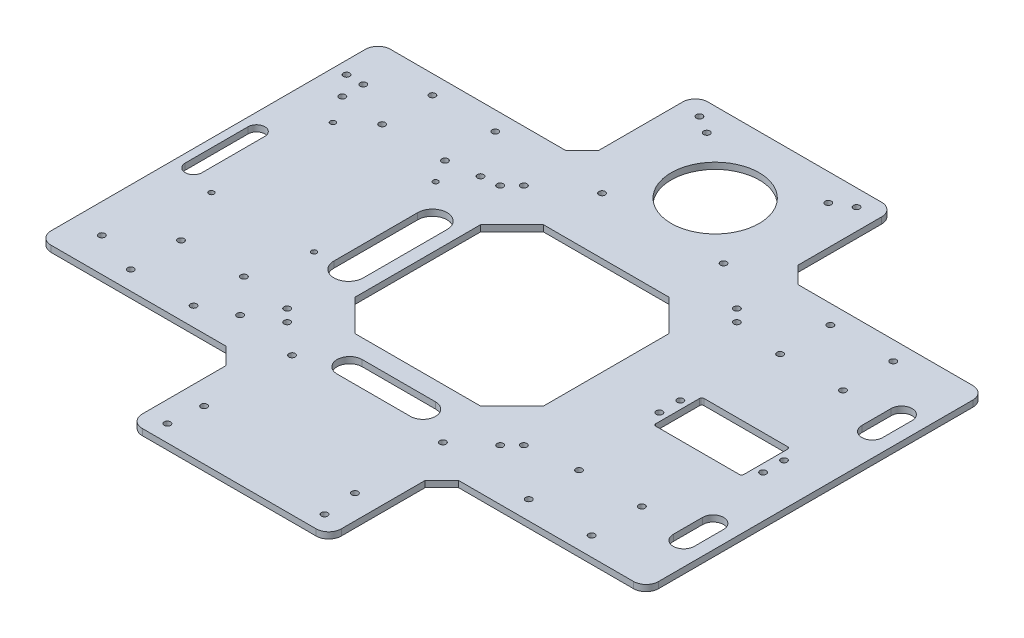
SolidWorks part; units mm, degrees
material "Thornel Mat VMA"
ref_plane "前视基准面" through (0, 0, 0) normal (0, 0, 1) x (1, 0, 0)
ref_plane "上视基准面" through (0, 0, 0) normal (0, 1, 0) x (1, 0, 0)
ref_plane "右视基准面" through (0, 0, 0) normal (1, 0, 0) x (0, 0, -1)
other "Configuration Table"
sketch "草图1" plane through (0, 0, 0) normal (0, 1, 0) x (1, 0, 0)
  line L0 (0, 0) -> (0, 135) construction
  line L1 (-145, -135) -> (145, -135)
  line L2 (-145, -135) -> (-145, 135)
  line L3 (-145, 135) -> (145, 135)
  line L4 (145, -135) -> (145, 135)
  line L5 (-145, -135) -> (145, 135) construction
  line L6 (-145, 135) -> (145, -135) construction
  line L7 (0, 0) -> (145, 0) construction
  line L8 (-47.5, 135) -> (-47.5, 81)
  line L9 (-47.5, 81) -> (-145, 81)
  line L10 (47.5, 81) -> (145, 81)
  line L11 (47.5, 135) -> (47.5, 81)
  line L12 (47.5, -81) -> (145, -81)
  line L13 (47.5, -135) -> (47.5, -81)
  line L14 (-47.5, -81) -> (-145, -81)
  line L15 (-47.5, -135) -> (-47.5, -81)
  point P0 (0, 0)
  dimension "D1" = 290
  dimension "D2" = 270
  dimension "D3" = 162
  dimension "D4" = 95
extrude "凸台-拉伸1" add sketch "草图1" along normal blind 3 contours L15 L1 L13 L12 L4 L10 L11 L3 L8 L9 L2 L14
sketch "草图2" plane through (0, 3, 0) normal (0, 1, 0) x (1, 0, 0)
  line L0 (0, 0) -> (145, 0) construction
  line L1 (145, -81) -> (145, 81) construction
  line L2 (0, 0) -> (0, 135) construction
  line L3 (-47.5, 135) -> (47.5, 135) construction
  line L4 (47.5, 81) -> (145, 81) construction
  circle A0 centre (110, 72) radius 1.5
  circle A1 centre (80, 72) radius 1.5
  circle A2 centre (80, 48) radius 1.5
  circle A3 centre (110, 48) radius 1.5
  circle A4 centre (110, -48) radius 1.5
  circle A5 centre (110, -72) radius 1.5
  circle A6 centre (80, -48) radius 1.5
  circle A7 centre (80, -72) radius 1.5
  circle A8 centre (-80, -72) radius 1.5
  circle A9 centre (-80, -48) radius 1.5
  circle A10 centre (-110, -72) radius 1.5
  circle A11 centre (-110, -48) radius 1.5
  circle A12 centre (-110, 48) radius 1.5
  circle A13 centre (-80, 48) radius 1.5
  circle A14 centre (-80, 72) radius 1.5
  circle A15 centre (-110, 72) radius 1.5
  dimension "D1" = 3
  dimension "D2" = 3
  dimension "D3" = 3
  dimension "D4" = 3
  dimension "D11" = 80
  dimension "D12" = 9
  dimension "D5" = 24
  dimension "D6" = 24
  dimension "D7" = 30
  dimension "D8" = 30
  dimension "D9" = 80
  dimension "D10" = 9
extrude "切除-拉伸1" cut sketch "草图2" against normal blind 3
sketch "草图3" plane through (0, 3, 0) normal (0, 1, 0) x (1, 0, 0)
  line L0 (0, 0) -> (0, 110.5115) construction
  line L1 (0, 0) -> (145, 0) construction
  line L2 (145, -81) -> (145, 81) construction
  line L3 (-86.4083, 97) -> (86.4083, 97) construction
  line L4 (0, 0) -> (0, 108.4938) construction
  line L7 (0, 0) -> (0, -114.288) construction
  circle A5 centre (0, 97) radius 21
  circle A33 centre (29, 122) radius 1.5
  circle A34 centre (29, 72) radius 1.5
  circle A35 centre (-29, 72) radius 1.5
  circle A36 centre (-29, 122) radius 1.5
  point P13 (0, 97)
  dimension "D2" = 97
  dimension "D6" = 42
  dimension "D12" = 25
  dimension "D8" = 3
  dimension "D5" = 0
  dimension "D9" = 29
extrude "切除-拉伸2" cut sketch "草图3" against normal blind 10
sketch "草图4" plane through (0, 3, 0) normal (0, 1, 0) x (1, 0, 0)
  line L1 (-45, -45) -> (45, -45)
  line L2 (-45, -45) -> (-45, 45)
  line L3 (-45, 45) -> (45, 45)
  line L4 (45, -45) -> (45, 45)
  line L5 (-45, -45) -> (45, 45) construction
  line L6 (-45, 45) -> (45, -45) construction
  point P0 (0, 0)
  dimension "D1" = 90
  dimension "D2" = 90
extrude "切除-拉伸3" cut sketch "草图4" against normal blind 3
fillet "圆角3" radius 6 8 edges at (-47.5, 1.5, -135) (47.5, 1.5, -135) (145, 1.5, -81) (145, 1.5, 81) (-47.5, 1.5, 135) (47.5, 1.5, 135) (-145, 1.5, 81) (-145, 1.5, -81)
chamfer "倒角1" distance 8 angle 45 4 edges at (47.5, 1.5, 81) (-47.5, 1.5, 81) (47.5, 1.5, -81) (-47.5, 1.5, -81)
sketch "草图7" plane through (0, 3, 0) normal (0, 1, 0) x (1, 0, 0)
  line L0 (0, 0) -> (0, 142.9478) construction
  line L1 (0, 0) -> (-184.5222, 0) construction
  line L2 (-137, -15) -> (-137, 15) construction
  line L5 (-58, -20) -> (-58, 20) construction
  line L6 (-65, -20) -> (-65, 20)
  line L7 (-51, -20) -> (-51, 20)
  line L8 (0, 0) -> (165.4514, 0) construction
  line L14 (-110, 0) -> (-110, 75.2826) construction
  line L15 (134, 38) -> (134, 52) construction
  line L33 (-141, -15) -> (-141, 15)
  line L34 (-133, -15) -> (-133, 15)
  line L35 (63, 0) -> (63, 55.2292) construction
  line L36 (0, -15) -> (172.3256, -15) construction
  line L38 (129, 38) -> (129, 52)
  line L39 (139, 38) -> (139, 52)
  line L40 (134, -38) -> (134, -52) construction
  line L41 (129, -38) -> (129, -52)
  line L42 (139, -38) -> (139, -52)
  arc A2 (-65, -20) -> (-51, -20) centre (-58, -20) ccw
  arc A3 (-51, 20) -> (-65, 20) centre (-58, 20) ccw
  arc A34 (-141, -15) -> (-133, -15) centre (-137, -15) ccw
  arc A35 (-133, 15) -> (-141, 15) centre (-137, 15) ccw
  arc A56 (129, 38) -> (139, 38) centre (134, 38) ccw
  arc A57 (139, 52) -> (129, 52) centre (134, 52) ccw
  arc A58 (129, -38) -> (139, -38) centre (134, -38) cw
  arc A59 (139, -52) -> (129, -52) centre (134, -52) cw
  point P6 (-137, 0)
  point P13 (-58, 0)
  point P21 (134, 45)
  point P37 (134, -45)
  dimension "D2" = 30
  dimension "D5" = 7
  dimension "D8" = 5
  dimension "D10" = 45
  dimension "D9" = 134
  dimension "D3" = 4
  dimension "D23" = 15
  dimension "D1" = 14
  dimension "D4" = 40
  dimension "D6" = 58
  dimension "D7" = 110
  dimension "D20" = 133
  dimension "D24" = 63
extrude "切除-拉伸6" cut sketch "草图7" against normal blind 10
chamfer "倒角2" distance 15 angle 45 4 edges at (45, 1.5, 45) (-45, 1.5, 45) (45, 1.5, -45) (-45, 1.5, -45)
sketch "草图8" plane through (0, 3, 0) normal (0, 1, 0) x (1, 0, 0)
  line L0 (0, 0) -> (0, 168.9929) construction
  line L1 (0, 0) -> (-169.1558, 0) construction
  line L2 (-103, 0) -> (-103, 65.828) construction
  line L3 (-103, -6) -> (-155.6162, -6) construction
  line L4 (0, 0) -> (-184.1789, 0) construction
  line L5 (0, 0) -> (0, 73.477) construction
  line L6 (-55.5, 81) -> (-139, 81) construction
  circle A15 centre (-139, 60) radius 1.5
  circle A16 centre (-131, 60) radius 1.5
  dimension "D2" = 8
  dimension "D4" = 103
  dimension "D5" = 6
  dimension "D6" = 0
  dimension "D7" = 3
  dimension "D8" = 3
  dimension "D11" = 28
  dimension "D12" = 36
  dimension "D10" = 21
extrude "切除-拉伸7" cut sketch "草图8" against normal blind 10
sketch "草图9" plane through (0, 3, 0) normal (0, 1, 0) x (1, 0, 0)
  line L0 (0, 0) -> (0, 165.3902) construction
  line L1 (0, 0) -> (179.4814, 0) construction
  line L2 (50.8431, 56.5) -> (56.5, 50.8431) construction
  line L3 (-62.5, -62.5) -> (62.5, -62.5) construction
  line L4 (-62.5, -62.5) -> (-62.5, 62.5) construction
  line L5 (-62.5, 62.5) -> (62.5, 62.5) construction
  line L6 (62.5, -62.5) -> (62.5, 62.5) construction
  line L7 (-62.5, -62.5) -> (62.5, 62.5) construction
  line L8 (-62.5, 62.5) -> (62.5, -62.5) construction
  line L18 (-50.3018, -50.3018) -> (40.4104, 40.4104) construction
  line L23 (-50.8431, -50.8431) -> (45.8431, 45.8431) construction
  line L24 (-48.3431, 48.3431) -> (48.3431, -48.3431) construction
  line L29 (-52.5221, -52.5221) -> (52.5221, 52.5221) construction
  line L30 (-52.5221, 52.5221) -> (52.5221, -52.5221) construction
  circle A0 centre (50.8431, 56.5) radius 1.5
  circle A1 centre (56.5, 50.8431) radius 1.5
  circle A2 centre (56.5, -50.8431) radius 1.5
  circle A3 centre (50.8431, -56.5) radius 1.5
  circle A4 centre (-50.8431, -56.5) radius 1.5
  circle A5 centre (-56.5, -50.8431) radius 1.5
  circle A6 centre (-56.5, 50.8431) radius 1.5
  circle A7 centre (-50.8431, 56.5) radius 1.5
  circle A8 centre (-37.5, -127) radius 1.5
  circle A9 centre (37.5, -127) radius 1.5
  circle A10 centre (37.5, 127) radius 1.5
  circle A11 centre (-37.5, 127) radius 1.5
  dimension "D3" = 3
  dimension "D4" = 3
  dimension "D6" = 8
  dimension "D9" = 3
  dimension "D11" = 127
  dimension "D1" = 125
  dimension "D2" = 125
  dimension "D5" = 45
  dimension "D7" = 6
  dimension "D8" = 6
  dimension "D10" = 37.5
extrude "切除-拉伸8" cut sketch "草图9" against normal blind 10
sketch "草图10" plane through (0, 3, 0) normal (0, 1, 0) x (1, 0, 0)
  line L0 (0, 0) -> (173.0266, 0) construction
  line L1 (0, 0) -> (0, 114.2255) construction
sketch "草图11" plane through (0, 3, 0) normal (0, 1, 0) x (1, 0, 0)
  line L0 (0, 0) -> (183.5565, 0) construction
  line L1 (0, 0) -> (0, -155.5612) construction
sketch "草图12" plane through (0, 3, 0) normal (0, 1, 0) x (1, 0, 0)
  line L0 (-17.5, -60) -> (17.5, -60) construction
  line L1 (0, 0) -> (0, -155.5612) construction
  line L2 (-17.5, -54) -> (17.5, -54)
  line L3 (-17.5, -66) -> (17.5, -66)
  line L4 (0, 0) -> (173.0266, 0) construction
  arc A0 (-17.5, -54) -> (-17.5, -66) centre (-17.5, -60) ccw
  arc A1 (17.5, -66) -> (17.5, -54) centre (17.5, -60) ccw
  point P4 (0, -60)
  dimension "D2" = 6
  dimension "D1" = 35
  dimension "D3" = 60
extrude "切除-拉伸9" cut sketch "草图12" against normal blind 10
sketch "草图14" plane through (0, 3, 0) normal (0, 1, 0) x (1, 0, 0)
  line L0 (0, 0) -> (0, -145.4864) construction
  line L1 (0, 0) -> (173.1076, 0) construction
  line L2 (0, -90) -> (89.1596, -90) construction
  circle A0 centre (36, -69) radius 1.5
  circle A1 centre (36, -111) radius 1.5
  circle A2 centre (-36, -111) radius 1.5
  circle A3 centre (-36, -69) radius 1.5
  dimension "D1" = 3
  dimension "D2" = 42
  dimension "D3" = 72
  dimension "D4" = 90
extrude "切除-拉伸10" cut sketch "草图14" against normal blind 10
sketch "草图15" plane through (0, 3, 0) normal (0, 1, 0) x (1, 0, 0)
  line L0 (0, 0) -> (175.5609, 0) construction
  line L1 (0, 0) -> (0, 158.0719) construction
  line L2 (100.11, 0) -> (100.11, 39.6302) construction
  line L3 (79.11, -11.5) -> (121.11, -11.5)
  line L4 (79.11, -11.5) -> (79.11, 11.5)
  line L5 (79.11, 11.5) -> (121.11, 11.5)
  line L6 (121.11, -11.5) -> (121.11, 11.5)
  line L7 (79.11, -11.5) -> (121.11, 11.5) construction
  line L8 (79.11, 11.5) -> (121.11, -11.5) construction
  line L9 (110, 0) -> (110, 79.3701) construction
  circle A0 centre (75.36, 5) radius 1.5
  circle A2 centre (75.36, -5) radius 1.5
  circle A4 centre (124.86, -5) radius 1.5
  circle A5 centre (124.86, 5) radius 1.5
  point P3 (100.11, 0)
  dimension "D3" = 10
  dimension "D4" = 3
  dimension "D5" = 49.5
  dimension "D1" = 42
  dimension "D2" = 23
  dimension "D6" = 9.89
  dimension "D7" = 110
extrude "切除-拉伸11" cut sketch "草图15" against normal blind 10
fillet "圆角4" radius 1 4 edges at (79.11, 1.5, 11.5) (121.11, 1.5, 11.5) (121.11, 1.5, -11.5) (79.11, 1.5, -11.5)
sketch "草图16" plane through (0, 3, 0) normal (0, 1, 0) x (1, 0, 0)
  line L0 (0, 8) -> (-202.0071, 8) construction
  line L1 (0, 8) -> (0, 203.0309) construction
  line L2 (-98, -6.3134) -> (-98, 94.9217) construction
  line L4 (0, 0) -> (0, 8) construction
  line L5 (0, 0) -> (-183.682, 0) construction
  circle A0 centre (-73.5, 37) radius 1.25
  circle A1 centre (-122.5, 37) radius 1.25
  circle A2 centre (-73.5, -21) radius 1.25
  circle A3 centre (-122.5, -21) radius 1.25
  dimension "D1" = 58
  dimension "D2" = 49
  dimension "D3" = 2.5
  dimension "D4" = 98
  dimension "D5" = 8
extrude "切除-拉伸12" cut sketch "草图16" against normal blind 10
sketch "草图19" plane through (0, 3, 0) normal (0, 1, 0) x (1, 0, 0)
  line L0 (0, 0) -> (-178.7427, 0) construction
  line L1 (0, 0) -> (0, 171.7177) construction
  line L2 (-98, -10.9053) -> (-98, 46.7773) construction
  line L3 (-98, -7.4) -> (-15.7423, -7.4) construction
  circle A0 centre (-65, 50) radius 1.5
  circle A1 centre (-131, 50) radius 1.5
  circle A2 centre (-65, -64.8) radius 1.5
  circle A3 centre (-131, -64.8) radius 1.5
  dimension "D1" = 3
  dimension "D2" = 114.8
  dimension "D3" = 66
  dimension "D4" = 98
  dimension "D5" = 7.4
extrude "切除-拉伸13" cut sketch "草图19" against normal blind 10
sketch "草图20" plane through (0, 3, 0) normal (0, 1, 0) x (1, 0, 0)
  line L0 (0, 0) -> (0, 140.7476) construction
  line L1 (0, 0) -> (-188.6657, 0) construction
  circle A0 centre (-60, 60) radius 1.5
  dimension "D1" = 3
  dimension "D2" = 60
  dimension "D3" = 60
sketch "草图21" plane through (0, 3, 0) normal (0, 1, 0) x (1, 0, 0)
  line L0 (-3, 0) -> (207.5032, 0) construction
  line L1 (-3, 0) -> (-3, -169.1707) construction
  line L2 (0, 0) -> (0, -166.304) construction
  line L3 (-48, -121.5) -> (42, -121.5) construction
  line L4 (-48, -121.5) -> (-48, -66.5) construction
  line L5 (-48, -66.5) -> (42, -66.5) construction
  line L6 (42, -121.5) -> (42, -66.5) construction
  line L7 (-48, -121.5) -> (42, -66.5) construction
  line L8 (-48, -66.5) -> (42, -121.5) construction
  line L9 (0, 0) -> (-28, 0) construction
  circle A0 centre (31, -84) radius 1.5
  circle A1 centre (32, -117.5) radius 1.5
  circle A2 centre (-28, -87.5) radius 1.5
  circle A3 centre (-28, -117.5) radius 1.5
  point P3 (-3, -94)
  dimension "D3" = 3
  dimension "D4" = 3
  dimension "D5" = 3
  dimension "D6" = 3
  dimension "D8" = 17.5
  dimension "D10" = 51
  dimension "D11" = 10
  dimension "D12" = 21
  dimension "D13" = 70
  dimension "D14" = 51
  dimension "D15" = 70
  dimension "D1" = 90
  dimension "D2" = 55
  dimension "D7" = 94
  dimension "D9" = 11
  dimension "D16" = 3
sketch "草图22" plane through (0, 3, 0) normal (0, 1, 0) x (1, 0, 0)
  line L0 (0, 0) -> (154.1719, 0) construction
  line L1 (61, 0) -> (61, 40.4074) construction
  circle A0 centre (73, 13) radius 1.5
  circle A1 centre (49, 13) radius 1.5
  circle A2 centre (73, -13) radius 1.5
  circle A3 centre (49, -13) radius 1.5
  dimension "D1" = 24
  dimension "D2" = 26
  dimension "D3" = 3
  dimension "D4" = 61
